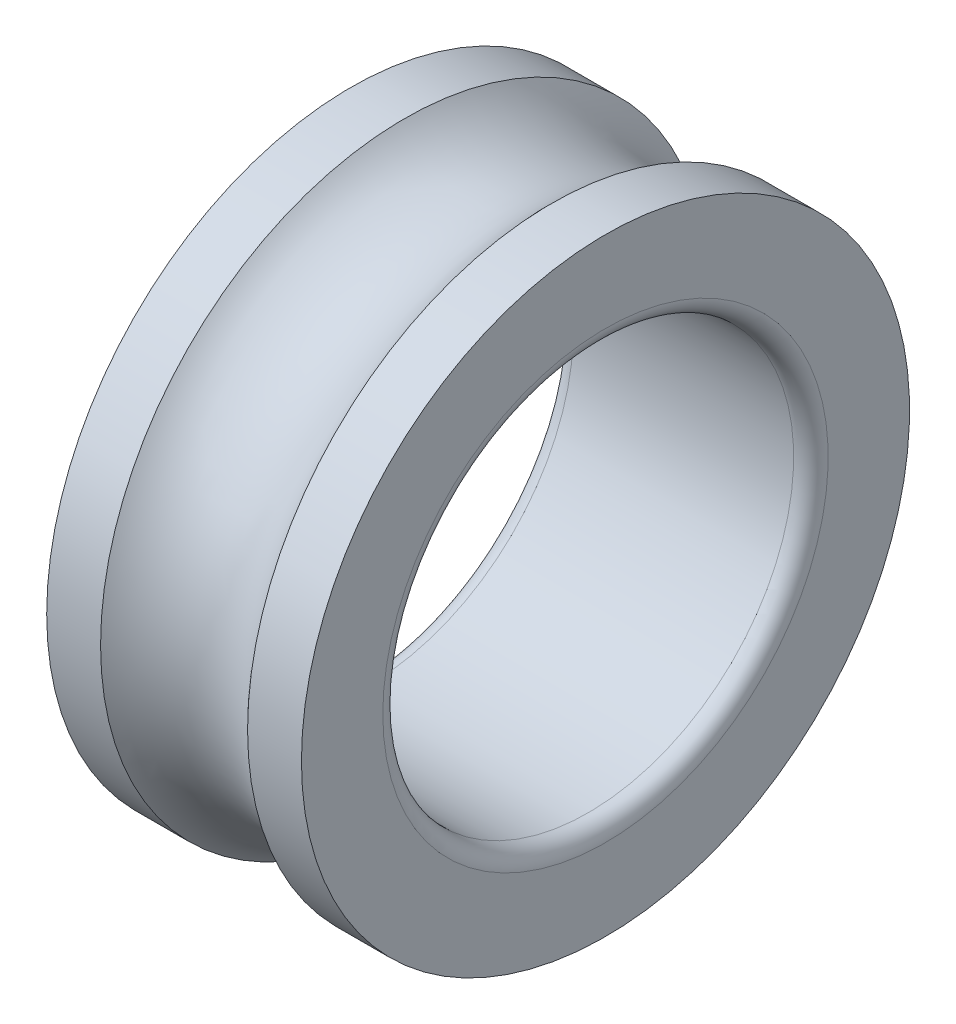
SolidWorks part; units mm, degrees
ref_plane "Front Plane" through (0, 0, 0) normal (0, 0, 1) x (1, 0, 0)
ref_plane "Top Plane" through (0, 0, 0) normal (0, 1, 0) x (1, 0, 0)
ref_plane "Right Plane" through (0, 0, 0) normal (1, 0, 0) x (0, 0, -1)
sketch "Sketch1" plane through (0, 0, 0) normal (0, 0, 1) x (1, 0, 0)
  line L0 (-46.3843, 0) -> (61.8843, 0) construction
  line L1 (0, 25) -> (0, -3.2966) construction
  line L2 (-13.4, 25) -> (13.4, 25)
  line L3 (-15.5, 27.1) -> (-15.5, 37)
  line L4 (-15.5, 37) -> (-8.9443, 37)
  line L5 (15.5, 27.1) -> (15.5, 37)
  line L6 (-15.5, 25) -> (15.5, 37) construction
  line L7 (-15.5, 37) -> (15.5, 25) construction
  line L8 (8.9443, 37) -> (15.5, 37)
  arc A0 (8.9443, 37) -> (-8.9443, 37) centre (0, 45) cw
  arc A1 (-13.4, 25) -> (-15.5, 27.1) centre (-13.4, 27.1) cw
  arc A2 (13.4, 25) -> (15.5, 27.1) centre (13.4, 27.1) ccw
  point P3 (0, 31)
  dimension "D4" = 12
  dimension "D6" = 2.1
  dimension "D1" = 31
  dimension "D2" = 37
  dimension "D3" = 25
  dimension "D5" = 8
revolve "Revolve1" add sketch "Sketch1" angle 360 about L0
